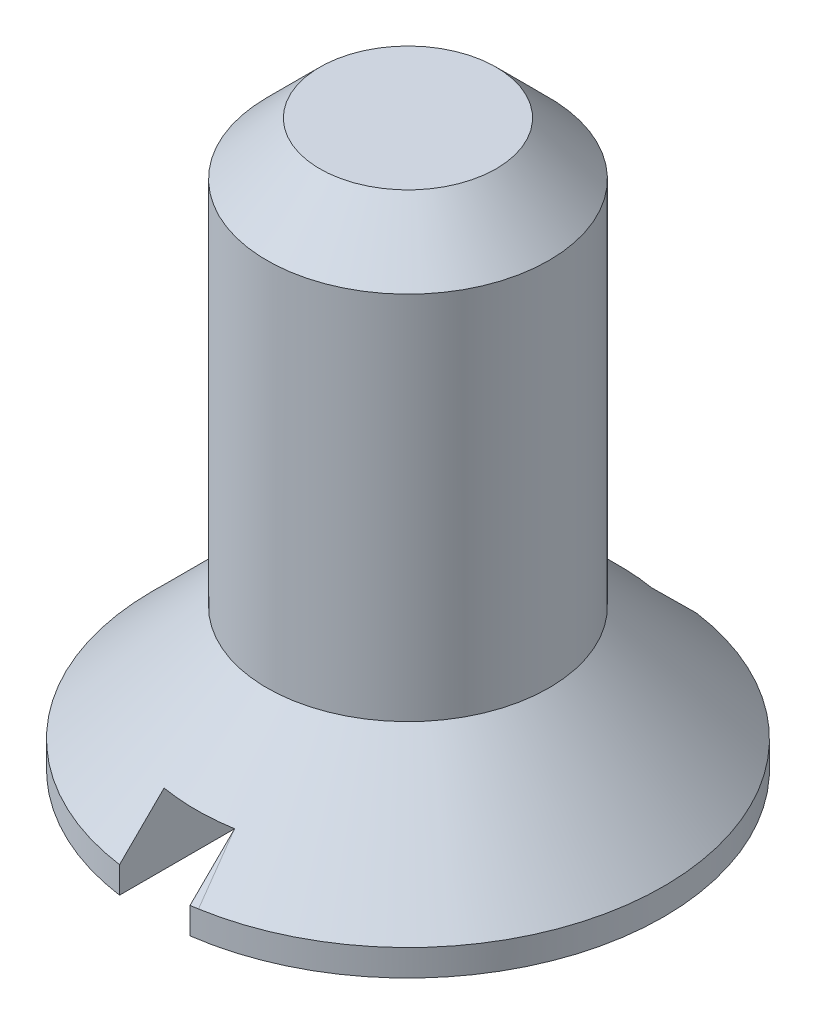
SolidWorks part; units mm, degrees
ref_plane "Спереди" through (0, 0, 0) normal (0, 0, 1) x (1, 0, 0)
ref_plane "Сверху" through (0, 0, 0) normal (0, 1, 0) x (1, 0, 0)
ref_plane "Справа" through (0, 0, 0) normal (1, 0, 0) x (0, 0, -1)
sketch "Эскиз1" plane through (0, 0, 0) normal (0, 0, 1) x (1, 0, 0)
  line L0 (0, 0) -> (-7.25, 0)
  line L1 (-7.25, 0) -> (-7.25, 0.75)
  line L2 (-7.25, 0.75) -> (-4, 4)
  line L3 (-4, 4) -> (-4, 16)
  line L4 (-4, 16) -> (0, 16)
  line L5 (0, 16) -> (0, 0)
  line L6 (-4, 4) -> (0, 4) construction
  dimension "D1" = 16
  dimension "D2" = 7.25
  dimension "D3" = 4
  dimension "D4" = 45
  dimension "D5" = 4
revolve "Повернуть1" add sketch "Эскиз1" angle 360 about L5
sketch "Эскиз2" plane through (0, 0, 0) normal (0, 0, 1) x (1, 0, 0)
  line L0 (-7.25, 0) -> (7.25, 0) construction
  line L1 (-1, 0) -> (1, 0)
  line L2 (-1, 0) -> (-1, 2)
  line L3 (-1, 2) -> (1, 2)
  line L4 (1, 0) -> (1, 2)
  dimension "D1" = 2
  dimension "D2" = 2
extrude "Вырез-Вытянуть1" cut sketch "Эскиз2" against normal mid plane 20
chamfer "Фаска1" distance 1.5 angle 45 1 edges at (-4, 16, 0)
